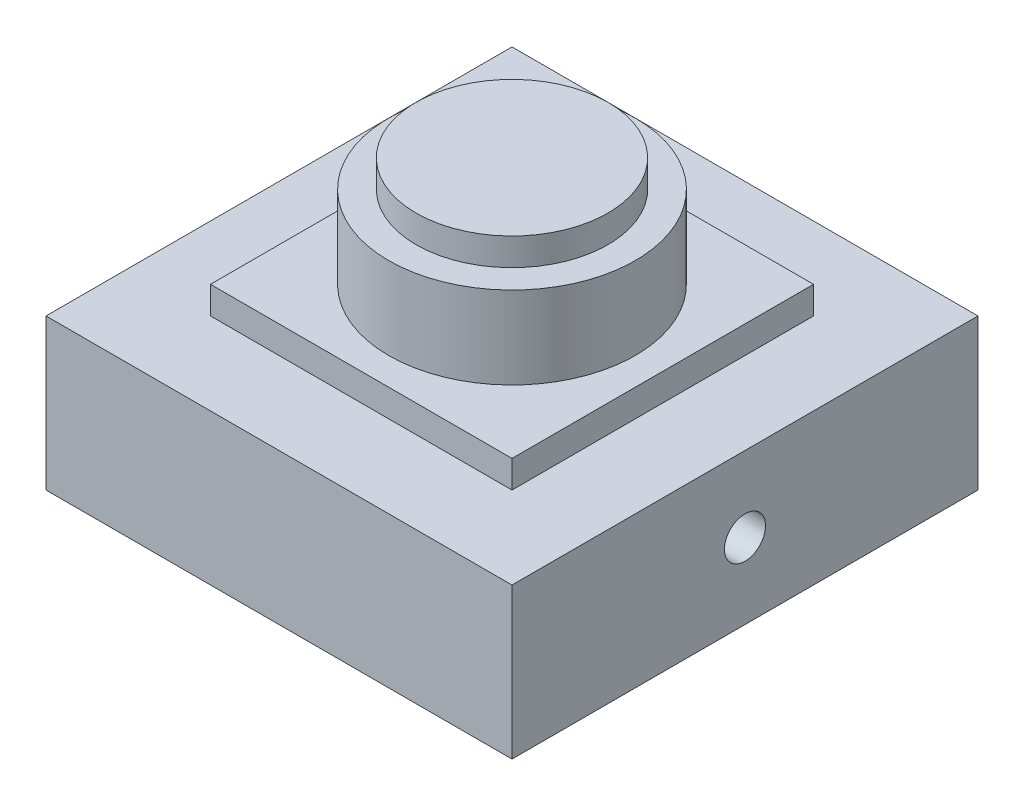
SolidWorks part; units mm, degrees
material "灰铸铁"
ref_plane "前视基准面" through (0, 0, 0) normal (0, 0, 1) x (1, 0, 0)
ref_plane "上视基准面" through (0, 0, 0) normal (0, 1, 0) x (1, 0, 0)
ref_plane "右视基准面" through (0, 0, 0) normal (1, 0, 0) x (0, 0, -1)
other "Configuration Table"
sketch "草图1" plane through (0, 0, 0) normal (0, 1, 0) x (1, 0, 0)
  line L1 (-17, -17) -> (17, -17)
  line L2 (-17, -17) -> (-17, 17)
  line L3 (-17, 17) -> (17, 17)
  line L4 (17, -17) -> (17, 17)
  line L5 (-17, -17) -> (17, 17) construction
  line L6 (-17, 17) -> (17, -17) construction
  point P0 (0, 0)
  dimension "D1" = 34
  dimension "D2" = 34
extrude "凸台-拉伸1" add sketch "草图1" along normal blind 11
sketch "草图2" plane through (0, 11, 0) normal (0, 1, 0) x (1, 0, 0)
  line L1 (-11, -11) -> (11, -11)
  line L2 (-11, -11) -> (-11, 11)
  line L3 (-11, 11) -> (11, 11)
  line L4 (11, -11) -> (11, 11)
  line L5 (-11, -11) -> (11, 11) construction
  line L6 (-11, 11) -> (11, -11) construction
  point P0 (0, 0)
  dimension "D1" = 22
  dimension "D2" = 22
extrude "凸台-拉伸2" add sketch "草图2" along normal blind 2
sketch "草图3" plane through (0, 13, 0) normal (0, 1, 0) x (1, 0, 0)
  circle A0 centre (0, 0) radius 9
  dimension "D1" = 18
extrude "凸台-拉伸3" add sketch "草图3" along normal blind 6
sketch "草图4" plane through (0, 19, 0) normal (0, 1, 0) x (1, 0, 0)
  circle A0 centre (0, 0) radius 7
  dimension "D1" = 14
extrude "凸台-拉伸4" add sketch "草图4" along normal blind 2
sketch "草图5" plane through (17, 0, 0) normal (1, 0, 0) x (0, 0, -1)
  line L0 (-17, 5.5) -> (19.5157, 5.5) construction
  line L1 (-17, 11) -> (-17, 0) construction
  line L2 (0, 5.5) -> (0, 0) construction
  circle A0 centre (0, 5.5) radius 1.5
  dimension "D1" = 3
extrude "切除-拉伸1" cut sketch "草图5" against normal up to surface (34 mm away) up to face at (-17, 5.5, 0)
